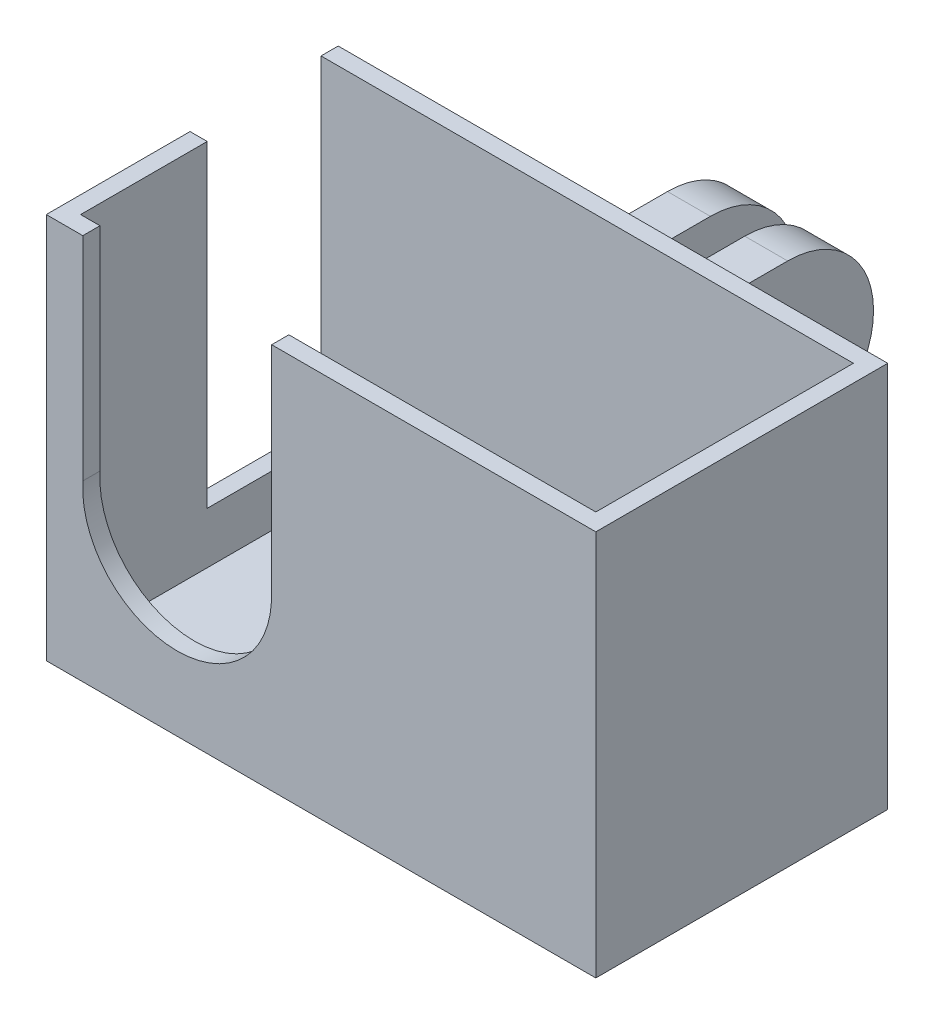
SolidWorks part; units mm, degrees
ref_plane "Front Plane" through (0, 0, 0) normal (0, 0, 1) x (1, 0, 0)
ref_plane "Top Plane" through (0, 0, 0) normal (0, 1, 0) x (1, 0, 0)
ref_plane "Right Plane" through (0, 0, 0) normal (1, 0, 0) x (0, 0, -1)
sketch "Sketch1" plane through (0, 0, 0) normal (0, 0, 1) x (1, 0, 0)
  line L1 (-30.3462, 18.505) -> (33.6538, 18.505)
  line L2 (-30.3462, 18.505) -> (-30.3462, -26.495)
  line L3 (-30.3462, -26.495) -> (33.6538, -26.495)
  line L4 (33.6538, 18.505) -> (33.6538, -26.495)
  dimension "D1" = 64
  dimension "D2" = 45
extrude "Boss-Extrude1" add sketch "Sketch1" along normal blind 34
sketch "Sketch3" plane through (0, 0, 34) normal (0, 0, 1) x (1, 0, 0)
  line L0 (-30.3462, 18.505) -> (-30.3462, -26.495) construction
  line L5 (-28.3462, 16.505) -> (31.6538, 16.505)
  line L6 (-28.3462, 16.505) -> (-28.3462, -24.495)
  line L7 (-28.3462, -24.495) -> (31.6538, -24.495)
  line L8 (31.6538, 16.505) -> (31.6538, -24.495)
  line L9 (33.6538, -26.495) -> (33.6538, 18.505) construction
  line L10 (33.6538, 18.505) -> (-30.3462, 18.505) construction
  line L11 (-30.3462, -26.495) -> (33.6538, -26.495) construction
  dimension "D1" = 2
  dimension "D2" = 2
  dimension "D3" = 2
  dimension "D4" = 2
extrude "Cut-Extrude2" cut sketch "Sketch3" against normal blind 27 from offset 2 offset against normal yes
sketch "Sketch4" plane through (0, 18.505, 0) normal (0, 1, 0) x (1, 0, 0)
  line L0 (-30.3462, -34) -> (-30.3462, 0) construction
  line L1 (-28.3462, -2) -> (31.6538, -2)
  line L2 (-28.3462, -2) -> (-28.3462, -32)
  line L3 (-28.3462, -32) -> (31.6538, -32)
  line L4 (31.6538, -2) -> (31.6538, -32)
  line L5 (33.6538, -34) -> (33.6538, 0) construction
  line L6 (-24.75, 0) -> (24.75, 0) construction
  line L7 (33.6538, -34) -> (-30.3462, -34) construction
  dimension "D1" = 2
  dimension "D2" = 2
  dimension "D3" = 2
  dimension "D4" = 2
extrude "Cut-Extrude3" cut sketch "Sketch4" against normal up to surface (43 mm away) up to face at (1.6538, -24.495, 18.5)
sketch "Sketch7" plane through (0, 0, 0) normal (1, 0, 0) x (0, 0, -1)
  line L1 (0, 7.9996) -> (15, 7.9996)
  line L2 (0, 7.9996) -> (0, -12.0004)
  line L3 (0, -12.0004) -> (15, -12.0004)
  arc A0 (15, 7.9996) -> (15, -12.0004) centre (15, -2.0004) cw
  dimension "D3" = 10
  dimension "D1" = 15
  dimension "D2" = 20
extrude "Boss-Extrude2" add sketch "Sketch7" along normal blind 5 from offset 2
sketch "Sketch8" plane through (0, 0, 0) normal (1, 0, 0) x (0, 0, -1)
  line L0 (0, -12.0004) -> (0, 7.9996)
  line L1 (0, 7.9996) -> (15, 7.9996)
  line L2 (0, -12.0004) -> (15, -12.0004)
  arc A0 (15, -12.0004) -> (15, 7.9996) centre (15, -2.0004) ccw
  dimension "D4" = 10
  dimension "D1" = 15
  dimension "D2" = 15
  dimension "D3" = 20
extrude "Boss-Extrude3" add sketch "Sketch8" against normal blind 5 from offset 2 offset against normal yes
sketch "Sketch10" plane through (-30.3462, 0, 0) normal (-1, 0, 0) x (0, 0, 1)
  line L2 (2, -18.495) -> (2, 18.505)
  line L3 (2, 18.505) -> (17.2555, 18.505)
  line L5 (34, 18.505) -> (0, 18.505) construction
  line L6 (17.2555, -18.495) -> (17.2555, 18.505)
  line L7 (0, 18.505) -> (0, -26.495) construction
  line L8 (2, -18.495) -> (17.2555, -18.495)
  line L9 (34, -26.495) -> (0, -26.495) construction
  dimension "D1" = 2
  dimension "D2" = 15.2555
  dimension "D3" = 8
extrude "Cut-Extrude5" cut sketch "Sketch10" against normal up to surface (2 mm away) up to face at (-28.3462, -2.995, 17)
sketch "Sketch15" plane through (0, 0, 34) normal (0, 0, 1) x (1, 0, 0)
  line L0 (33.6538, 18.505) -> (-30.3462, 18.505) construction
  line L1 (-26.0928, 18.505) -> (-4.0928, 18.505)
  line L2 (-26.0928, 18.505) -> (-26.0928, -7.495)
  line L3 (-26.0928, -7.495) -> (-4.0928, -7.495)
  line L4 (-4.0928, 18.505) -> (-4.0928, -7.495)
  dimension "D1" = 26
  dimension "D2" = 22
extrude "Cut-Extrude6" cut sketch "Sketch15" against normal offset from surface (10 mm away) 10 up to face at (1.6538, -3.995, 34)
sketch "Sketch20" plane through (0, 0, 34) normal (0, 0, 1) x (1, 0, 0)
  circle A0 centre (-15.1121, -6.8898) radius 11
  dimension "D1" = 22
extrude "Cut-Extrude7" cut sketch "Sketch20" against normal offset from surface (10 mm away) 10 up to face at (-6.7195, 0.755, 34)
